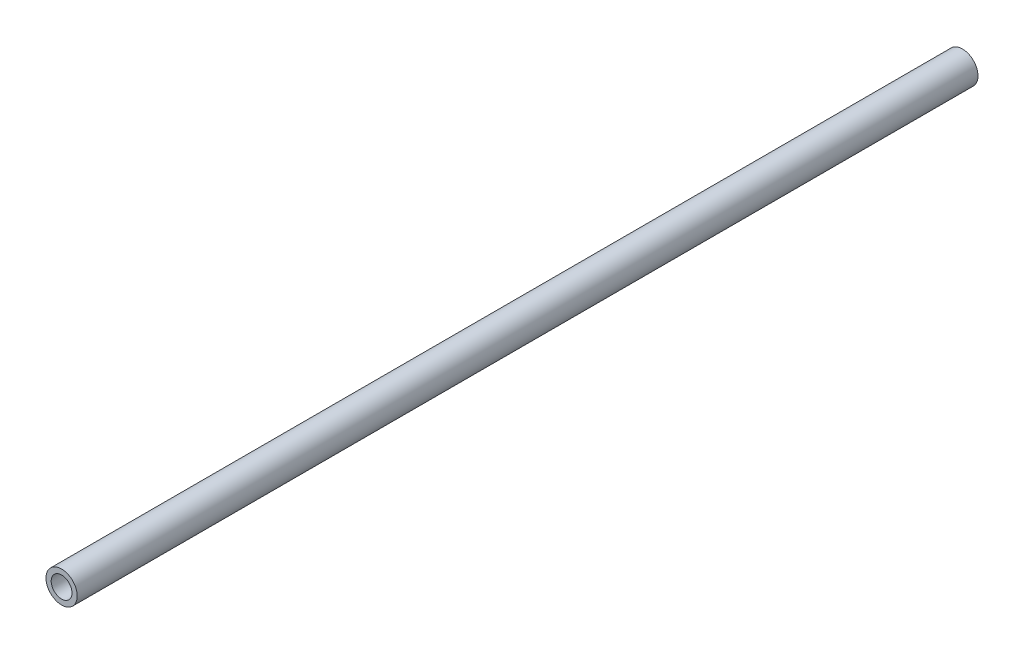
SolidWorks part; units mm, degrees
material "Tubi carbonio"
ref_plane "Piano frontale" through (0, 0, 0) normal (0, 0, 1) x (1, 0, 0)
ref_plane "Piano superiore" through (0, 0, 0) normal (0, 1, 0) x (1, 0, 0)
ref_plane "Piano destro" through (0, 0, 0) normal (1, 0, 0) x (0, 0, -1)
sketch "Schizzo1" plane through (0, 0, 0) normal (0, 0, 1) x (1, 0, 0)
  circle A0 centre (0, 0) radius 3
  circle A1 centre (0, 0) radius 2
  dimension "D1" = 4
  dimension "D2" = 6
extrude "Estrusione-Estrusione1" add sketch "Schizzo1" along normal blind 173
